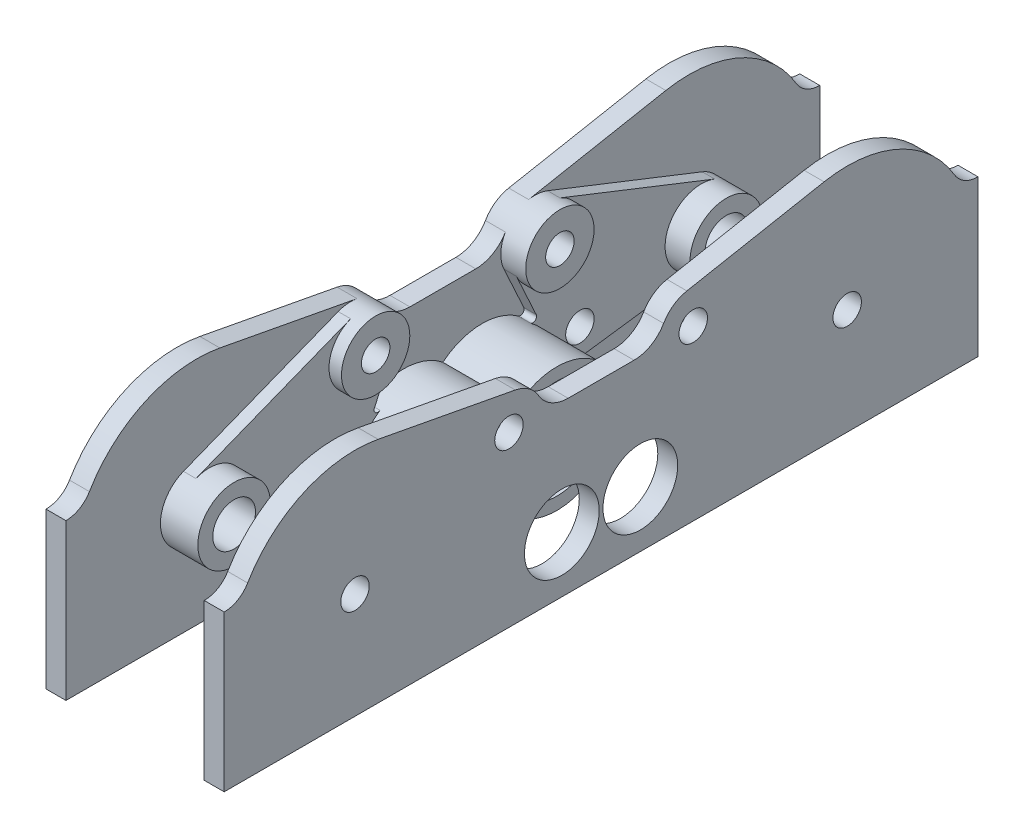
SolidWorks part; units mm, degrees
ref_plane "Front Plane" through (0, 0, 0) normal (0, 0, 1) x (1, 0, 0)
ref_plane "Top Plane" through (0, 0, 0) normal (0, 1, 0) x (1, 0, 0)
ref_plane "Right Plane" through (0, 0, 0) normal (1, 0, 0) x (0, 0, -1)
sketch "Sketch1" plane through (0, 0, 0) normal (1, 0, 0) x (0, 0, -1)
  line L0 (0, -23) -> (-73.7154, -23) construction
  line L1 (-39.5, -3.0695) -> (-39.5, -12.9305)
  line L2 (-26.9, -3.0695) -> (-26.9, -12.9305)
  line L3 (0, 23) -> (-79.1129, 23) construction
  line L5 (-3.7063, 19.6536) -> (-25.7287, 15.5005)
  line L6 (-34.2141, 10.1095) -> (-39.5, 10.1095)
  line L7 (0, -17) -> (-39.5, -17)
  line L8 (-39.5, -17) -> (-39.5, 10.1095)
  line L9 (21, 8) -> (21, -17)
  line L10 (0, -17) -> (21, -17)
  circle A0 centre (0, 0) radius 2.286
  circle A1 centre (-24.7121, 10.1095) radius 2.286
  arc A2 (-26.9, -3.0695) -> (-39.5, -3.0695) centre (-33.2, -8) ccw
  circle A3 centre (0, 0) radius 23 construction
  arc A4 (-39.5, -12.9305) -> (-26.9, -12.9305) centre (-33.2, -8) ccw
  circle A5 centre (-24.7121, 10.1095) radius 13.5 construction
  circle A6 centre (0, 0) radius 20
  arc A7 (-25.7287, 15.5005) -> (-29.4631, 12.8525) centre (-24.7121, 10.1095) ccw
  arc A8 (-29.4631, 12.8525) -> (-34.2141, 10.1095) centre (-34.2141, 15.5955) cw
  arc A9 (17.2308, 10.1538) -> (21, 8) centre (21, 12.375) ccw
  point P5 (-25.5337, 7.805)
  point P13 (-25.1133, -11.4266)
  point P17 (-24.7121, 23.6095)
  point P18 (-26.8541, -3.2194)
  point P20 (-27.1956, -4.2)
  point P29 (-28.9638, -13.2326)
  point P33 (-23.4209, -4.7565)
  point P36 (-24.4835, 10.5686)
  point P37 (-28.2012, -11.9467)
  point P38 (-33.2295, -7.5)
  point P39 (-28.2012, -11.6634)
  point P40 (-25.5453, 7.7671)
  point P41 (-32.663, 5)
  point P42 (-24.7268, 10.2797)
  point P43 (-33.1587, 10)
  point P44 (-25.1421, 8.9868)
  point P45 (-25.329, 8.4458)
  point P46 (0, 0)
  point P47 (0, 0)
  point P48 (0, 0)
  point P49 (0, -16.8893)
  point P50 (0, 0)
  point P51 (-24.9831, 9.4199)
  point P52 (0, 0)
  point P53 (-37, 8.7)
  point P54 (0, 0)
  point P55 (-24.8843, 9.678)
  point P56 (0, 0)
  point P57 (0, 0)
  point P58 (-33.9672, 10.6932)
  dimension "D2" = 4.572
  dimension "D3" = 4.572
  dimension "D4" = 46
  dimension "D8" = 17
  dimension "D9" = 9
  dimension "D11" = 40
  dimension "D12" = 25
  dimension "D13" = 3.2
  dimension "D14" = 21
  dimension "D16" = 20
  dimension "D5" = 16
  dimension "D7" = 27
  dimension "D6" = 12.6
  dimension "D10" = 26.7
  dimension "D15" = 60.5
extrude "Boss-Extrude1" add sketch "Sketch1" along normal blind 3.2
mirror "Mirror1" about plane through (3.2, 0, 39.5) normal (0, 0, 1) of bodies 101
sketch "Sketch4" plane through (3.2, 0, 0) normal (1, 0, 0) x (0, 0, -1)
  circle A0 centre (-54.2879, 10.1095) radius 2.286
  circle A1 centre (-24.7121, 10.1095) radius 2.286
  circle A2 centre (-24.7121, 10.1095) radius 2.286 construction
  circle A3 centre (-54.2879, 10.1095) radius 2.286 construction
  circle A4 centre (-54.2879, 10.1095) radius 5.486
  circle A5 centre (-24.7121, 10.1095) radius 5.486
extrude "Boss-Extrude2" add sketch "Sketch4" along normal blind 4
sketch "Sketch5" plane through (3.2, 0, 0) normal (1, 0, 0) x (0, 0, -1)
  circle A0 centre (-79, 0) radius 3.429
  circle A1 centre (0, 0) radius 3.429
  dimension "D1" = 6.858
extrude "Extrude-Thin2" add sketch "Sketch5" along normal blind 6 thin
sketch "Sketch7" plane through (0, 0, 0) normal (-1, 0, 0) x (0, 0, 1)
  line L6 (25.7287, 15.5005) -> (3.7063, 19.6536)
  line L7 (-21, 8) -> (-21, -17)
  line L8 (-21, -17) -> (100, -17)
  line L9 (100, -17) -> (100, 8)
  line L10 (75.2937, 19.6536) -> (53.2713, 15.5005)
  line L11 (44.7859, 10.1095) -> (34.2141, 10.1095)
  line L12 (25.7287, 15.5005) -> (3.7063, 19.6536)
  line L13 (-21, 8) -> (-21, -17)
  line L14 (-21, -17) -> (100, -17)
  line L15 (100, -17) -> (100, 8)
  line L16 (75.2937, 19.6536) -> (53.2713, 15.5005)
  line L17 (44.7859, 10.1095) -> (34.2141, 10.1095)
  arc A8 (29.4631, 12.8525) -> (25.7287, 15.5005) centre (24.7121, 10.1095) ccw
  arc A9 (3.7063, 19.6536) -> (-17.2308, 10.1538) centre (0, 0) ccw
  arc A10 (-21, 8) -> (-17.2308, 10.1538) centre (-21, 12.375) ccw
  arc A11 (96.2308, 10.1538) -> (100, 8) centre (100, 12.375) ccw
  arc A12 (96.2308, 10.1538) -> (75.2937, 19.6536) centre (79, 0) ccw
  arc A13 (53.2713, 15.5005) -> (49.5369, 12.8525) centre (54.2879, 10.1095) ccw
  arc A14 (44.7859, 10.1095) -> (49.5369, 12.8525) centre (44.7859, 15.5955) ccw
  arc A15 (29.4631, 12.8525) -> (34.2141, 10.1095) centre (34.2141, 15.5955) ccw
  arc A16 (29.4631, 12.8525) -> (25.7287, 15.5005) centre (24.7121, 10.1095) ccw
  arc A17 (3.7063, 19.6536) -> (-17.2308, 10.1538) centre (0, 0) ccw
  arc A18 (-21, 8) -> (-17.2308, 10.1538) centre (-21, 12.375) ccw
  arc A19 (96.2308, 10.1538) -> (100, 8) centre (100, 12.375) ccw
  arc A20 (96.2308, 10.1538) -> (75.2937, 19.6536) centre (79, 0) ccw
  arc A21 (53.2713, 15.5005) -> (49.5369, 12.8525) centre (54.2879, 10.1095) ccw
  arc A22 (44.7859, 10.1095) -> (49.5369, 12.8525) centre (44.7859, 15.5955) ccw
  arc A23 (29.4631, 12.8525) -> (34.2141, 10.1095) centre (34.2141, 15.5955) ccw
  dimension "D1" = 0
extrude "Boss-Extrude3" add sketch "Sketch7" against normal blind 3.2 from offset 25.4 separate body offset against normal yes
sketch "Sketch8" plane through (25.4, 0, 0) normal (-1, 0, 0) x (0, 0, 1)
  circle A0 centre (79, 0) radius 2.286 construction
  circle A1 centre (54.2879, 10.1095) radius 2.286 construction
  circle A2 centre (24.7121, 10.1095) radius 2.286 construction
  circle A3 centre (0, 0) radius 2.286 construction
  circle A4 centre (79, 0) radius 2.286
  circle A5 centre (54.2879, 10.1095) radius 2.286
  circle A6 centre (24.7121, 10.1095) radius 2.286
  circle A7 centre (0, 0) radius 2.286
extrude "Cut-Extrude1" cut sketch "Sketch8" against normal through all
sketch "Sketch9" plane through (25.4, 0, 0) normal (-1, 0, 0) x (0, 0, 1)
  circle A0 centre (79, 0) radius 2.286 construction
  circle A1 centre (0, 0) radius 2.286 construction
  circle A2 centre (79, 0) radius 2.286
  circle A3 centre (0, 0) radius 2.286
extrude "Extrude-Thin3" add sketch "Sketch9" along normal blind 4 thin
sketch "Sketch10" plane through (0, 0, 0) normal (-1, 0, 0) x (0, 0, 1)
  line L0 (19.5, -4.3) -> (59.5, -4.3) construction
  line L1 (-21, -17) -> (100, -17) construction
  circle A0 centre (19.5, -4.3) radius 2.286
  circle A1 centre (59.5, -4.3) radius 2.286
  point P4 (39.5, -4.3)
  point P7 (39.5, -17)
  dimension "D1" = 4.572
  dimension "D2" = 12.7
  dimension "D3" = 40
extrude "Cut-Extrude2" cut sketch "Sketch10" against normal blind 12
ref_plane "Plane1" through (0, 0, 39.5) normal (0, 0, -1) x (-1, 0, 0)
sketch "Sketch13" plane through (3.2, 0, 0) normal (1, 0, 0) x (0, 0, -1)
  line L0 (-81.1376, 5.4229) -> (-56.2997, 15.2133)
  line L1 (-79.7867, -5.7757) -> (-60.0668, -8.4616)
  line L2 (-55.6843, -6.055) -> (-49.3038, 7.8171)
  circle A2 centre (-79, 0) radius 5.829 construction
  circle A3 centre (-59.5, -4.3) radius 2.286 construction
  circle A4 centre (-54.2879, 10.1095) radius 5.486 construction
  arc A5 (-81.1376, 5.4229) -> (-79.7867, -5.7757) centre (-79, 0) ccw
  circle A6 centre (-59.5, -4.3) radius 2.286
  arc A7 (-49.3038, 7.8171) -> (-56.2997, 15.2133) centre (-54.2879, 10.1095) ccw
  circle A8 centre (-59.5, -4.3) radius 2.286
  circle A9 centre (-79, 0) radius 3.429
  circle A10 centre (-54.2879, 10.1095) radius 2.2825
  circle A11 centre (-59.5, -4.3) radius 2.286
  arc A13 (-60.0668, -8.4616) -> (-55.6843, -6.055) centre (-59.5, -4.3) ccw
  circle A14 centre (-79, 0) radius 5.829 construction
  point P21 (0, 0)
  circle M5 centre (-59.5, -4.3) radius 2.286
  circle M8 centre (-79, 0) radius 5.829
  arc M31 (-49.5369, 12.8525) -> (-53.2713, 15.5005) centre (-54.2879, 10.1095) cw
  dimension "D1" = 4.2
extrude "Boss-Extrude6" add sketch "Sketch13" along normal blind 2 contours L1 A13 L2 L0 M31 M8 M5
mirror "Mirror3" about plane through (0, 0, 39.5) normal (0, 0, -1) of "Boss-Extrude6"
sketch "Sketch14" plane through (3.2, 0, 0) normal (1, 0, 0) x (0, 0, -1)
  line L0 (-26.9, -3.0695) -> (-26.9, -12.9305) construction
  line L1 (-52.1, -3.0695) -> (-52.1, -12.9305) construction
  line L2 (-26.9, -3.0695) -> (-26.9, -12.9305)
  line L3 (-52.1, -3.0695) -> (-52.1, -12.9305)
  arc A0 (-52.1, -12.9305) -> (-39.5, -12.9305) centre (-45.8, -8) ccw construction
  arc A1 (-39.5, -12.9305) -> (-26.9, -12.9305) centre (-33.2, -8) ccw construction
  arc A2 (-26.9, -3.0695) -> (-39.5, -3.0695) centre (-33.2, -8) ccw construction
  arc A3 (-39.5, -3.0695) -> (-52.1, -3.0695) centre (-45.8, -8) ccw construction
  arc A4 (-52.1, -12.9305) -> (-39.5, -12.9305) centre (-45.8, -8) ccw
  arc A5 (-39.5, -12.9305) -> (-26.9, -12.9305) centre (-33.2, -8) ccw
  arc A6 (-26.9, -3.0695) -> (-39.5, -3.0695) centre (-33.2, -8) ccw
  arc A7 (-39.5, -3.0695) -> (-52.1, -3.0695) centre (-45.8, -8) ccw
extrude "Extrude-Thin5" add sketch "Sketch14" along normal blind 12 and the other way up to surface thin other way up to face at (0, -4.3, 61.786) thin type one direction wall 2
fillet "Fillet2" radius 0.6 4 edges at (4.2, -2.0676, 25.1497) (4.2, -2.0676, 53.8503) (4.2, -2.6106, 54.1) (4.2, -2.6106, 24.9)
sketch "Sketch15" plane through (28.6, 0, 0) normal (1, 0, 0) x (0, 0, -1)
  circle A0 centre (-45.8, -8) radius 6
  circle A1 centre (-33.2, -8) radius 6
  dimension "D1" = 12
extrude "Cut-Extrude3" cut sketch "Sketch15" against normal blind 6
